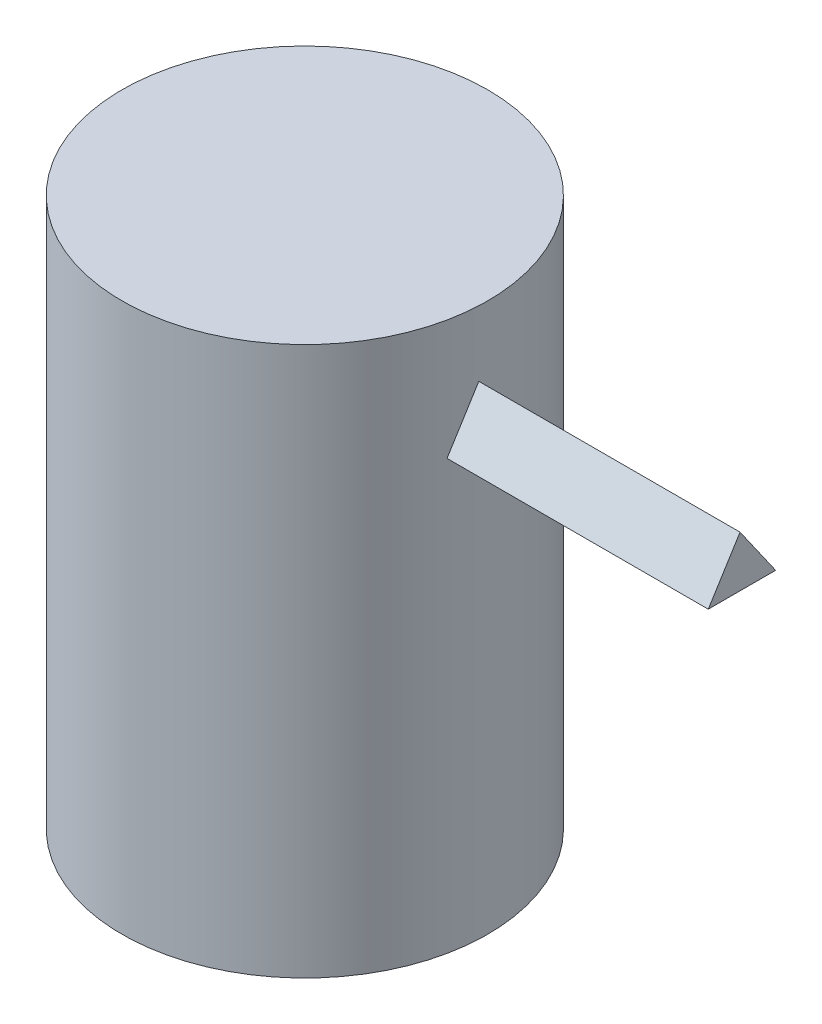
SolidWorks part; units mm, degrees
material "AISI 1020"
ref_plane "Front Plane" through (0, 0, 0) normal (0, 0, 1) x (1, 0, 0)
ref_plane "Top Plane" through (0, 0, 0) normal (0, 1, 0) x (1, 0, 0)
ref_plane "Right Plane" through (0, 0, 0) normal (1, 0, 0) x (0, 0, -1)
sketch "Sketch1" plane through (0, 0, 0) normal (0, 1, 0) x (1, 0, 0)
  circle A1 centre (0, 0) radius 7
  dimension "D2" = 14
extrude "Boss-Extrude1" add sketch "Sketch1" along normal blind 21
shell "Shell2" thickness 1
ref_plane "Plane1" through (7, 0, 0) normal (1, 0, 0) x (0, 0, -1)
sketch "Sketch3" plane through (7, 0, 0) normal (1, 0, 0) x (0, 0, -1)
  line L0 (-0.3406, 18.5036) -> (-1.5569, 16.5575)
  line L1 (-1.5569, 16.5575) -> (1.0217, 16.5575)
  line L2 (1.0217, 16.5575) -> (-0.3406, 18.5036)
extrude "Boss-Extrude2" add sketch "Sketch3" along normal blind 10 separate body
